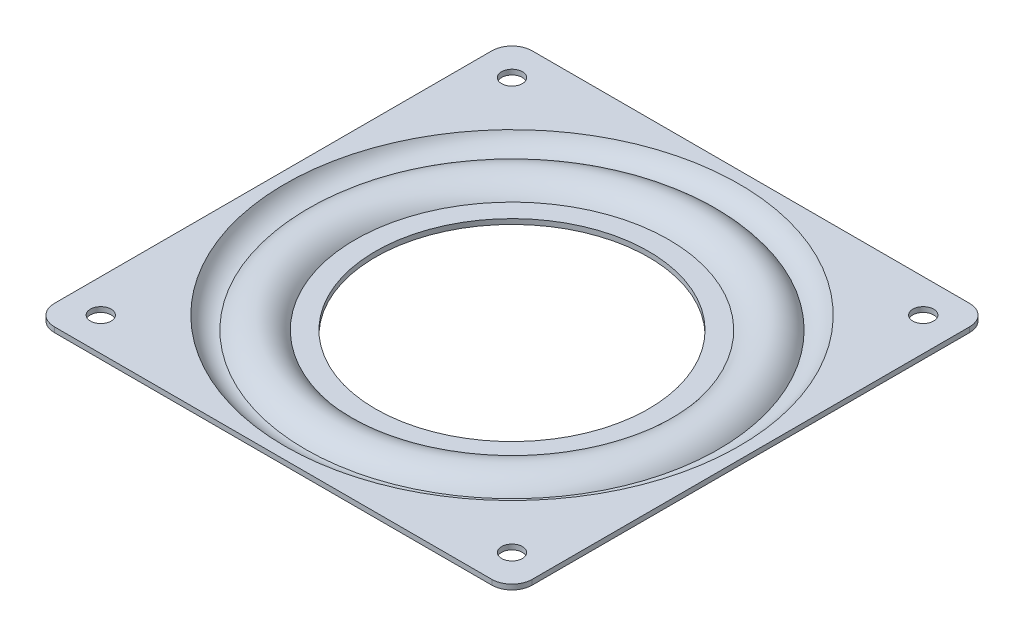
SolidWorks part; units mm, degrees
ref_plane "前视基准面" through (0, 0, 0) normal (0, 0, 1) x (1, 0, 0)
ref_plane "上视基准面" through (0, 0, 0) normal (0, 1, 0) x (1, 0, 0)
ref_plane "右视基准面" through (0, 0, 0) normal (1, 0, 0) x (0, 0, -1)
sketch "草图1" plane through (0, 0, 0) normal (0, 0, 1) x (1, 0, 0)
  line L0 (-36.7805, 0) -> (-35.9228, 0)
  line L1 (0, 6.9172) -> (0, -6.9172) construction
  line L2 (-31, -2.5698) -> (-27, -2.5698)
  line L3 (-35.9228, 0) -> (0, 0) construction
  line L4 (0, 0) -> (43.3864, 0) construction
  line L5 (-43.3864, 0) -> (-36.7805, 0) construction
  line L6 (-31.5531, -3.5698) -> (-27, -3.5698)
  line L7 (-27, -2.5698) -> (-27, -3.5698)
  line L8 (-44.9105, 0) -> (-45.8139, -0.4289)
  arc A0 (-44.9105, 0) -> (-40.8455, -2.5698) centre (-40.8455, 1.9302) ccw
  arc A1 (-40.8455, -2.5698) -> (-31, -2.5698) centre (-35.9228, -6) cw
  arc A2 (-40.8455, -2.5698) -> (-36.8127, -0.0664) centre (-40.8455, 1.9302) ccw construction
  arc A3 (-36.8127, -0.0664) -> (-36.7805, 0) centre (-40.8455, 1.9302) ccw
  arc A4 (-45.8139, -0.4289) -> (-40.2759, -3.5402) centre (-40.8455, 1.9302) ccw
  arc A5 (-40.2759, -3.5402) -> (-31.5531, -3.5698) centre (-35.9228, -6) cw
  point P4 (0, 0)
  point P8 (0, 0)
  dimension "D1" = 4.5
  dimension "D2" = 6
  dimension "D3" = 27
  dimension "D4" = 4
revolve "旋转1" add sketch "草图1" angle 360 about L1
sketch "草图2" plane through (0, 0, 0) normal (0, 1, 0) x (1, 0, 0)
  line L0 (0, 0) -> (-40.6586, 40.6586) construction
  line L1 (-43.25, 47.25) -> (47.25, 47.25)
  line L2 (-47.25, 43.25) -> (-47.25, -47.25)
  line L3 (-47.25, -47.25) -> (47.25, -47.25)
  line L4 (47.25, 47.25) -> (47.25, -47.25)
  line L5 (-47.25, 47.25) -> (47.25, -47.25) construction
  line L6 (-47.25, -47.25) -> (47.25, 47.25) construction
  line L7 (0, 0) -> (40.6586, 40.6586) construction
  line L8 (0, 0) -> (-43.25, 43.25) construction
  circle A0 centre (0, 0) radius 44.9105 construction
  circle A1 centre (0, 0) radius 44.9105
  arc A2 (-43.25, 47.25) -> (-47.25, 43.25) centre (-43.25, 43.25) ccw
  circle A3 centre (-40.6586, 40.6586) radius 2.05
  circle A4 centre (40.6586, 40.6586) radius 2.05
  circle A5 centre (40.6586, -40.6586) radius 2.05
  circle A6 centre (-40.6586, -40.6586) radius 2.05
  arc A7 (47.25, 43.25) -> (43.25, 47.25) centre (43.25, 43.25) ccw
  arc A8 (43.25, -47.25) -> (47.25, -43.25) centre (43.25, -43.25) ccw
  arc A9 (-47.25, -43.25) -> (-43.25, -47.25) centre (-43.25, -43.25) ccw
  dimension "D3" = 4
  dimension "D4" = 4.1
  dimension "D9" = 4
  dimension "D1" = 94.5
  dimension "D2" = 94.5
  dimension "D5" = 57.5
  dimension "D7" = 90
  dimension "D8" = 57.5
  dimension "D10" = 61.1647
  dimension "D6" = 4
extrude "凸台-拉伸1" add sketch "草图2" against normal blind 1 contours L2 A9 L3 A8 L4 A7 L1 A2 A6 A5 A4 A3 A1
sketch "Sketch2" plane through (0, -1, 0) normal (0, -1, 0) x (1, 0, 0)
  line L0 (-40.6586, 40.6586) -> (-40.6586, 38.6086) construction
  circle A0 centre (-40.6586, 40.6586) radius 2.05 construction
